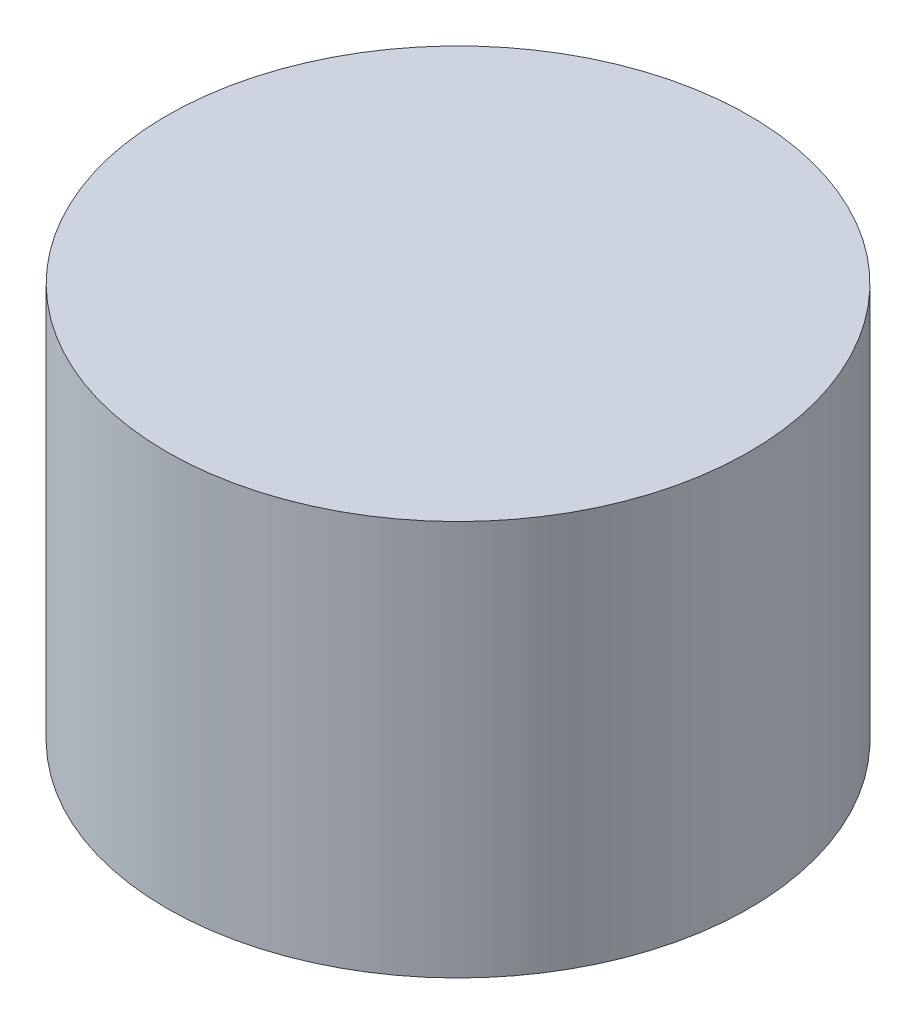
SolidWorks part; units mm, degrees
ref_plane "前视基准面" through (0, 0, 0) normal (0, 0, 1) x (1, 0, 0)
ref_plane "上视基准面" through (0, 0, 0) normal (0, 1, 0) x (1, 0, 0)
ref_plane "右视基准面" through (0, 0, 0) normal (1, 0, 0) x (0, 0, -1)
sketch "草图1" plane through (0, 0, 0) normal (0, 1, 0) x (1, 0, 0)
  circle A0 centre (0, 0) radius 14
extrude "凸台-拉伸1" add sketch "草图1" along normal blind 19
